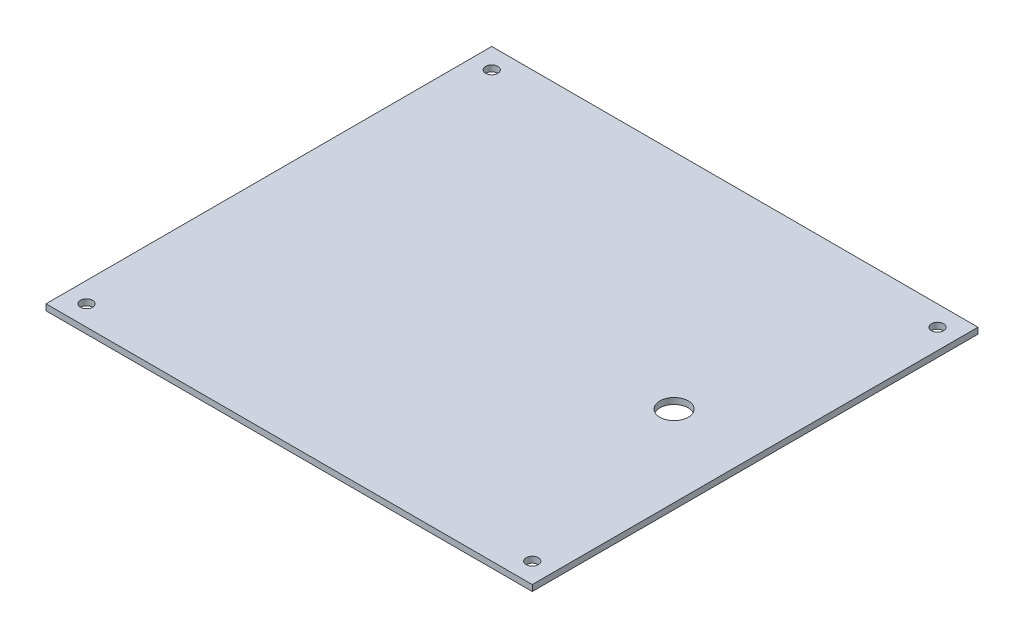
SolidWorks part; units mm, degrees
ref_plane "Front Plane" through (0, 0, 0) normal (0, 0, 1) x (1, 0, 0)
ref_plane "Top Plane" through (0, 0, 0) normal (0, 1, 0) x (1, 0, 0)
ref_plane "Right Plane" through (0, 0, 0) normal (1, 0, 0) x (0, 0, -1)
sketch "Sketch1" plane through (0, 0, 0) normal (0, 1, 0) x (1, 0, 0)
  line L0 (0, 55) -> (120, 55) construction
  line L1 (0, 0) -> (120, 0)
  line L2 (0, 0) -> (0, 110)
  line L3 (0, 110) -> (120, 110)
  line L4 (120, 0) -> (120, 110)
  circle A0 centre (100, 55) radius 3.5
  circle A1 centre (5, 105) radius 1.5
  circle A2 centre (115, 105) radius 1.5
  circle A3 centre (5, 5) radius 1.5
  circle A4 centre (115, 5) radius 1.5
  point P5 (100, 55)
  dimension "D4" = 7
  dimension "D5" = 3
  dimension "D6" = 3
  dimension "D7" = 3
  dimension "D8" = 3
  dimension "D9" = 5
  dimension "D10" = 5
  dimension "D11" = 5
  dimension "D12" = 5
  dimension "D13" = 5
  dimension "D14" = 5
  dimension "D15" = 5
  dimension "D16" = 5
  dimension "D1" = 110
  dimension "D2" = 120
  dimension "D3" = 20
extrude "Boss-Extrude1" add sketch "Sketch1" along normal blind 1.5
